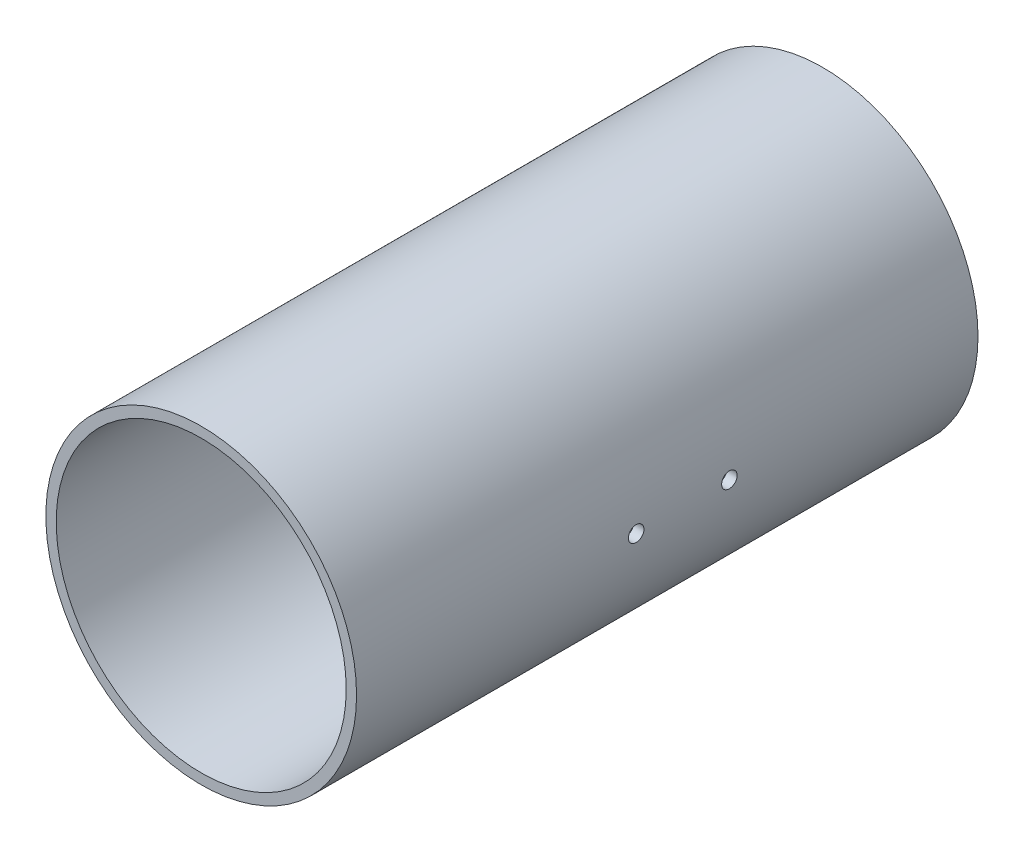
SolidWorks part; units mm, degrees
ref_plane "Front Plane" through (0, 0, 0) normal (0, 0, 1) x (1, 0, 0)
ref_plane "Top Plane" through (0, 0, 0) normal (0, 1, 0) x (1, 0, 0)
ref_plane "Right Plane" through (0, 0, 0) normal (1, 0, 0) x (0, 0, -1)
sketch "Sketch1" plane through (0, 0, 0) normal (0, 0, 1) x (1, 0, 0)
  circle A0 centre (0, 0) radius 30
  circle A1 centre (0, 0) radius 28
  dimension "D1" = 60
  dimension "D2" = 2
extrude "Boss-Extrude1" add sketch "Sketch1" along normal blind 120
sketch "Sketch2" plane through (0, 0, 0) normal (1, 0, 0) x (0, 0, -1)
  line L0 (0, 0) -> (-120, 0) construction
  line L1 (-120, 30) -> (-120, -30) construction
  line L2 (-120, 0) -> (0, 0) construction
  line L3 (0, -30) -> (0, 30) construction
  circle A0 centre (-48, 0) radius 1.5
  circle A1 centre (-66, 0) radius 1.5
  point P9 (0, 0)
  dimension "D1" = 3
  dimension "D2" = 18
  dimension "D3" = 48
extrude "Cut-Extrude1" cut sketch "Sketch2" against normal through all both and the other way through all
